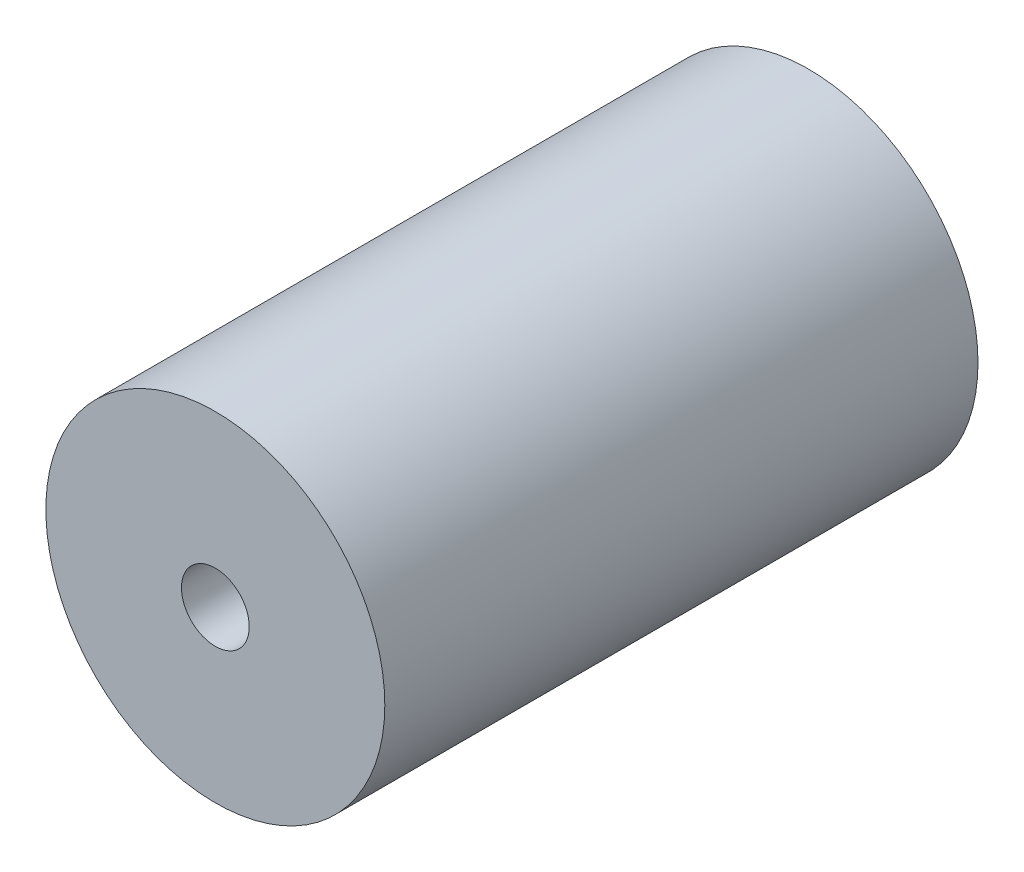
SolidWorks part; units mm, degrees
ref_plane "Спереди" through (0, 0, 0) normal (0, 0, 1) x (1, 0, 0)
ref_plane "Сверху" through (0, 0, 0) normal (0, 1, 0) x (1, 0, 0)
ref_plane "Справа" through (0, 0, 0) normal (1, 0, 0) x (0, 0, -1)
sketch "Эскиз2" plane through (0, 0, 0) normal (0, 0, 1) x (1, 0, 0)
  circle A0 centre (0, 0) radius 10
  circle A1 centre (0, 0) radius 2
  dimension "D1" = 20
  dimension "D2" = 4
extrude "Бобышка-Вытянуть1" add sketch "Эскиз2" along normal blind 35 contours A0 | A1
